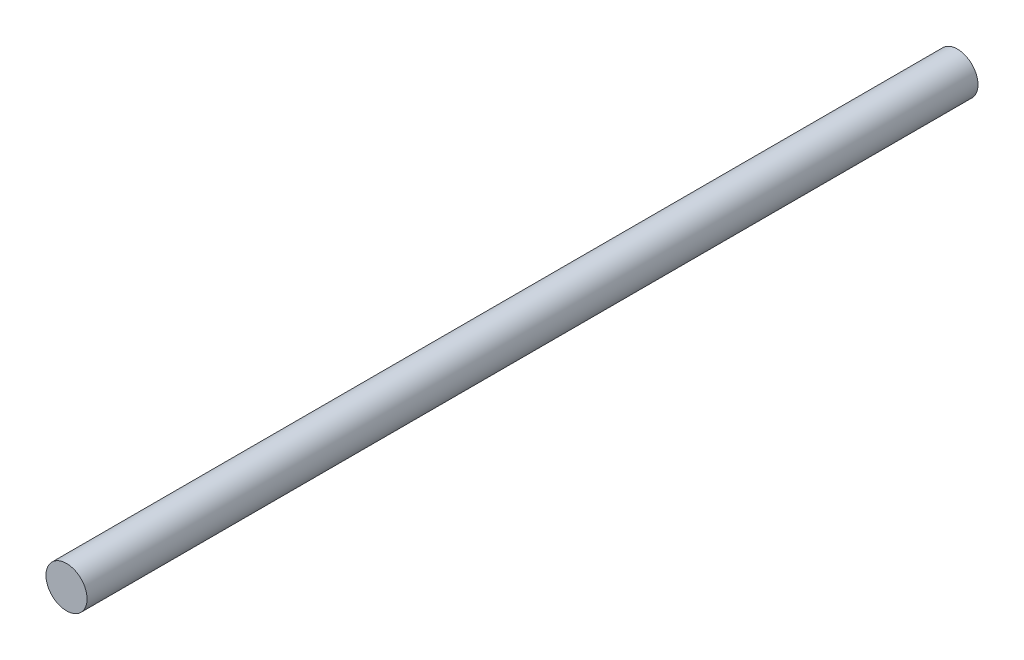
SolidWorks part; units mm, degrees
ref_plane "Front Plane" through (0, 0, 0) normal (0, 0, 1) x (1, 0, 0)
ref_plane "Top Plane" through (0, 0, 0) normal (0, 1, 0) x (1, 0, 0)
ref_plane "Right Plane" through (0, 0, 0) normal (1, 0, 0) x (0, 0, -1)
sketch "Sketch1" plane through (0, 0, 0) normal (0, 0, 1) x (1, 0, 0)
  circle A0 centre (0, 0) radius 7.62
  dimension "D1" = 15.24
extrude "Boss-Extrude1" add sketch "Sketch1" along normal blind 330.2
